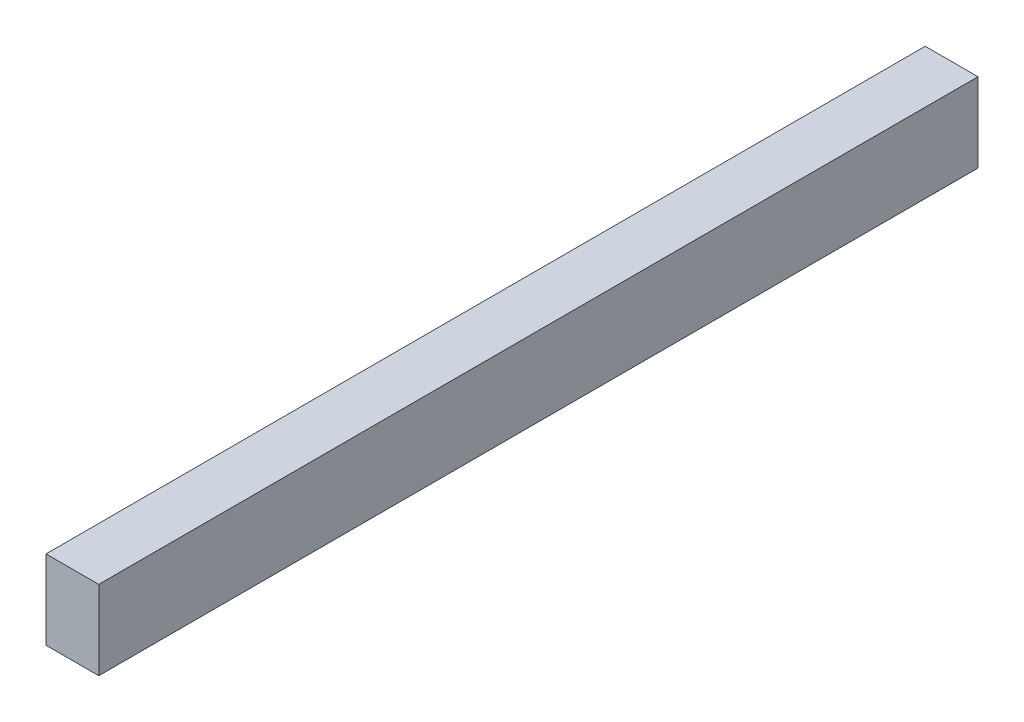
SolidWorks part; units mm, degrees
ref_plane "Front Plane" through (0, 0, 0) normal (0, 0, 1) x (1, 0, 0)
ref_plane "Top Plane" through (0, 0, 0) normal (0, 1, 0) x (1, 0, 0)
ref_plane "Right Plane" through (0, 0, 0) normal (1, 0, 0) x (0, 0, -1)
sketch "Sketch1" plane through (0, 0, 0) normal (1, 0, 0) x (0, 0, -1)
  line L5 (-250, -22.5) -> (250, -22.5)
  line L6 (-250, -22.5) -> (-250, 22.5)
  line L7 (-250, 22.5) -> (250, 22.5)
  line L8 (250, -22.5) -> (250, 22.5)
  line L9 (-250, -22.5) -> (250, 22.5) construction
  line L10 (-250, 22.5) -> (250, -22.5) construction
  point P0 (0, 0)
  dimension "D1" = 500
  dimension "D2" = 45
extrude "Boss-Extrude1" add sketch "Sketch1" against normal blind 30
sketch "Sketch2" plane through (0, -22.5, 0) normal (0, -1, 0) x (1, 0, 0)
  line L0 (-30, 250) -> (0, 250) construction
  line L15 (-23, 243) -> (-7, 243)
  line L16 (-23, 243) -> (-23, -167)
  line L17 (-23, -167) -> (-7, -167)
  line L18 (-7, 243) -> (-7, -167)
  line L19 (-15, 250) -> (-15, -250) construction
  line L20 (-30, -250) -> (0, -250) construction
  point P10 (-15, 243)
  dimension "D1" = 16
  dimension "D2" = 7
  dimension "D4" = 410
extrude "Cut-Extrude1" cut sketch "Sketch2" against normal blind 13
sketch "Sketch3" plane through (0, 0, -250) normal (0, 0, -1) x (-1, 0, 0)
  line L0 (30, 22.5) -> (0, 22.5) construction
  line L1 (15, 22.5) -> (15, -22.5) construction
  line L2 (30, -22.5) -> (0, -22.5) construction
  line L3 (0, 0) -> (30, 0) construction
  line L4 (30, -22.5) -> (30, 22.5) construction
  circle A1 centre (15, 0) radius 3.8
  dimension "D1" = 7.6
extrude "Cut-Extrude2" cut sketch "Sketch3" against normal blind 95
sketch "Sketch4" plane through (0, -9.5, 0) normal (0, -1, 0) x (1, 0, 0)
  line L0 (-15, 243) -> (-15, -167) construction
  line L2 (-7, 243) -> (-23, 243) construction
  line L3 (-23, -167) -> (-7, -167) construction
  circle A0 centre (-15, -162) radius 5
  point P4 (0, 0)
  dimension "D1" = 10
extrude "Cut-Extrude3" cut sketch "Sketch4" against normal blind 12
sketch "Sketch5" plane through (0, -9.5, 0) normal (0, -1, 0) x (1, 0, 0)
  line L0 (-15, -167) -> (-7, -167) construction
  line L1 (-21.5, -167) -> (-8.5, -167)
  line L2 (-21.5, -167) -> (-21.5, -157)
  line L3 (-21.5, -157) -> (-8.5, -157)
  line L4 (-8.5, -167) -> (-8.5, -157)
  line L5 (-21.5, -167) -> (-8.5, -157) construction
  line L6 (-21.5, -157) -> (-8.5, -167) construction
  line L7 (-23, 243) -> (-23, -167) construction
  point P0 (-15, -162)
  dimension "D1" = 1.5
extrude "Cut-Extrude4" cut sketch "Sketch5" against normal blind 6
